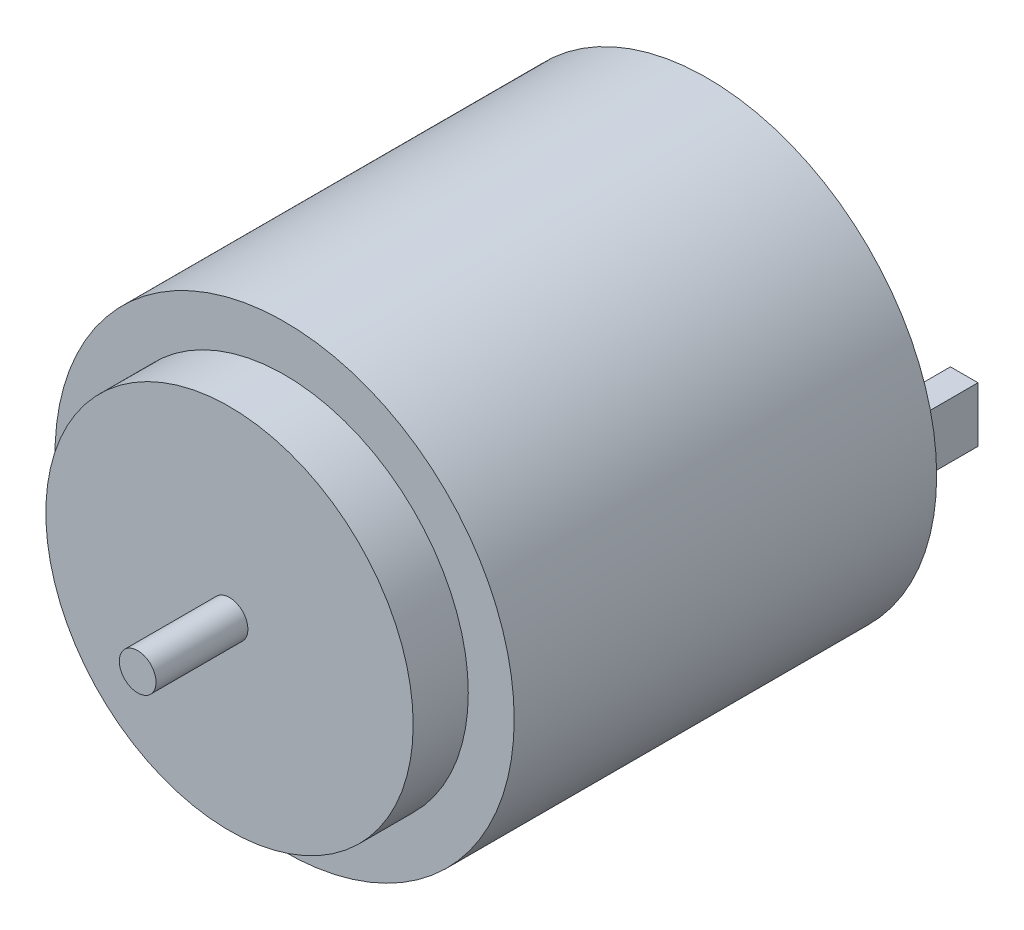
SolidWorks part; units mm, degrees
ref_plane "Plan de face" through (0, 0, 0) normal (0, 0, 1) x (1, 0, 0)
ref_plane "Plan de dessus" through (0, 0, 0) normal (0, 1, 0) x (1, 0, 0)
ref_plane "Plan de droite" through (0, 0, 0) normal (1, 0, 0) x (0, 0, -1)
sketch "Esquisse1" plane through (0, 0, 0) normal (0, 0, 1) x (1, 0, 0)
  circle A0 centre (-60.7801, 28.5357) radius 12.5
extrude "Boss.-Extru.1" add sketch "Esquisse1" along normal blind 23
sketch "Esquisse2" plane through (0, 0, 23) normal (0, 0, 1) x (1, 0, 0)
  line L0 (-60.7801, 41.0357) -> (-60.7801, 16.0357) construction
  circle A0 centre (-60.7801, 28.5357) radius 12.5 construction
  circle A1 centre (-60.7801, 28.5357) radius 10
extrude "Boss.-Extru.2" add sketch "Esquisse2" along normal blind 3
sketch "Esquisse3" plane through (0, 0, 26) normal (0, 0, 1) x (1, 0, 0)
  line L0 (-60.7801, 38.5357) -> (-60.7801, 18.5357) construction
  line L1 (-60.7801, 29.5357) -> (-60.7801, 28.5357) construction
  circle A0 centre (-60.7801, 28.5357) radius 10 construction
  circle A1 centre (-60.7801, 28.5357) radius 1
  point P8 (-60.7801, 28.5357)
  point P11 (-64.7282, 29.1782)
  point P36 (-60.7801, 28.5357)
  dimension "D1" = 2
extrude "Boss.-Extru.3" add sketch "Esquisse3" along normal blind 5 contours A1
sketch "Esquisse4" plane through (0, 0, 0) normal (0, 0, -1) x (-1, 0, 0)
  line L0 (48.2801, 28.5357) -> (73.2801, 28.5357) construction
  line L1 (60.7801, 41.0357) -> (60.7801, 16.0357) construction
  line L2 (70.0301, 27.0357) -> (70.0301, 30.0357)
  line L3 (50.0301, 27.0357) -> (51.5301, 27.0357)
  line L4 (50.0301, 27.0357) -> (50.0301, 30.0357)
  line L5 (50.0301, 30.0357) -> (51.5301, 30.0357)
  line L6 (51.5301, 27.0357) -> (51.5301, 30.0357)
  line L7 (50.0301, 27.0357) -> (51.5301, 30.0357) construction
  line L8 (50.0301, 30.0357) -> (51.5301, 27.0357) construction
  line L9 (71.5301, 27.0357) -> (70.0301, 27.0357)
  line L10 (71.5301, 27.0357) -> (70.0301, 30.0357) construction
  line L11 (71.5301, 30.0357) -> (70.0301, 27.0357) construction
  line L12 (71.5301, 27.0357) -> (71.5301, 30.0357)
  line L13 (71.5301, 30.0357) -> (70.0301, 30.0357)
  circle A0 centre (60.7801, 28.5357) radius 12.5 construction
  point P7 (50.7801, 28.5357)
  point P12 (60.7801, 28.5357)
  dimension "D1" = 3
  dimension "D2" = 1.5
  dimension "D3" = 10
extrude "Boss.-Extru.4" add sketch "Esquisse4" along normal blind 4
